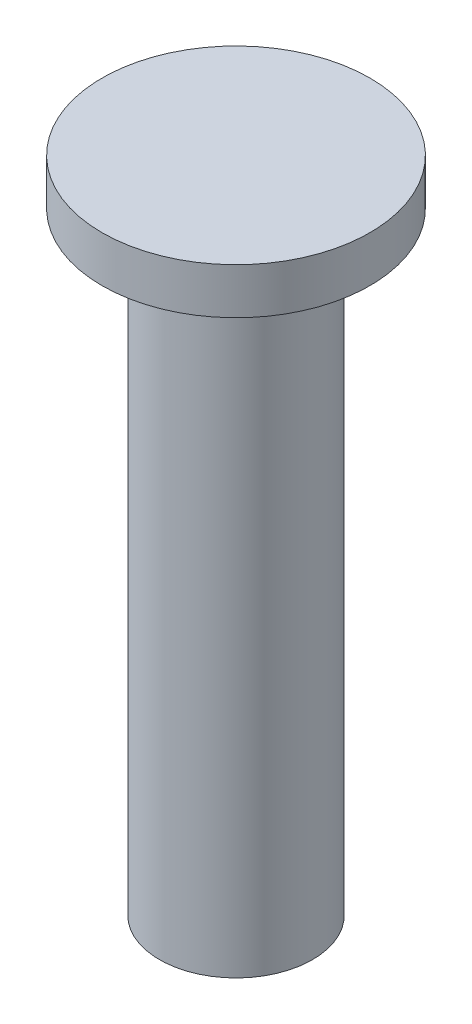
SolidWorks part; units mm, degrees
material "AISI 304"
ref_plane "前视基准面" through (0, 0, 0) normal (0, 0, 1) x (1, 0, 0)
ref_plane "上视基准面" through (0, 0, 0) normal (0, 1, 0) x (1, 0, 0)
ref_plane "右视基准面" through (0, 0, 0) normal (1, 0, 0) x (0, 0, -1)
other "Configuration Table"
sketch "草图1" plane through (0, 0, 0) normal (0, 1, 0) x (1, 0, 0)
  circle A0 centre (0, 0) radius 3.5
  dimension "D1" = 7
extrude "凸台-拉伸1" add sketch "草图1" along normal blind 1.2
sketch "草图2" plane through (0, 0, 0) normal (0, -1, 0) x (1, 0, 0)
  circle A0 centre (0, 0) radius 2
  dimension "D1" = 4
extrude "凸台-拉伸2" add sketch "草图2" along normal blind 16
